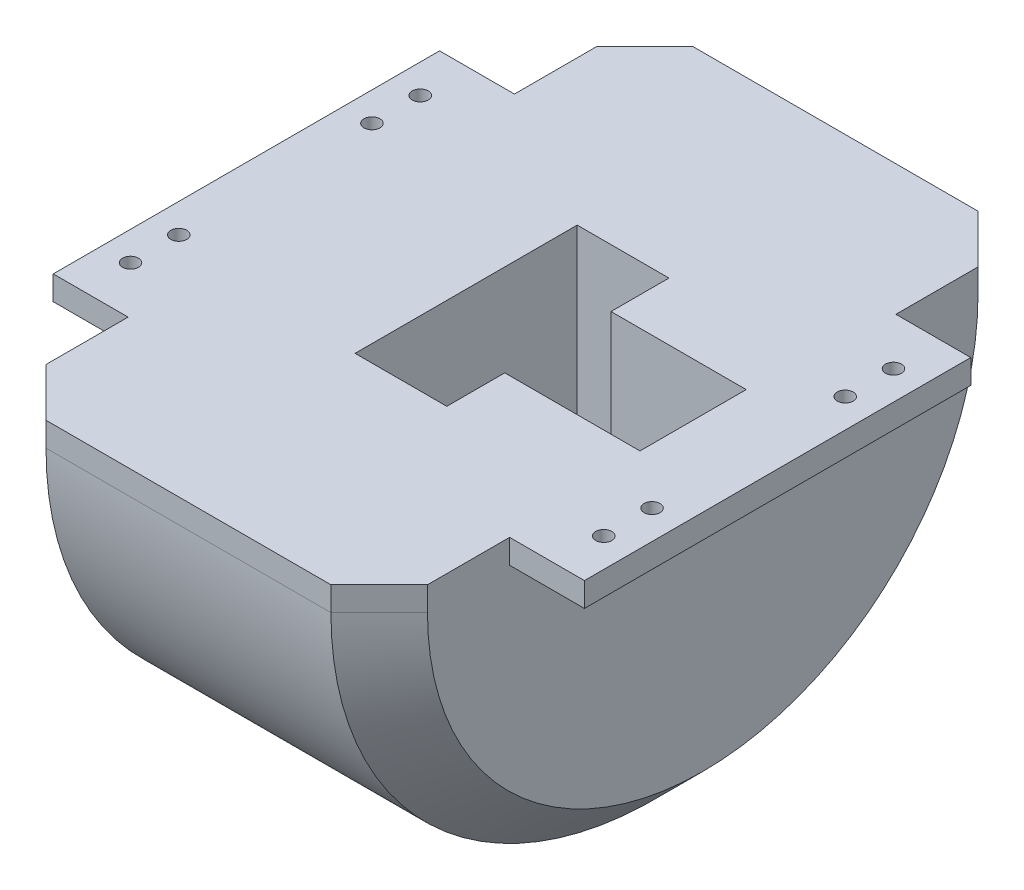
SolidWorks part; units mm, degrees
ref_plane "Front Plane" through (0, 0, 0) normal (0, 0, 1) x (1, 0, 0)
ref_plane "Top Plane" through (0, 0, 0) normal (0, 1, 0) x (1, 0, 0)
ref_plane "Right Plane" through (0, 0, 0) normal (1, 0, 0) x (0, 0, -1)
sketch "Sketch2" plane through (0, 0, 0) normal (0, 1, 0) x (1, 0, 0)
  line L0 (0, 0) -> (16.0378, 0) construction
  line L1 (-55, 40) -> (55, 40)
  line L2 (-55, 40) -> (-55, -40)
  line L3 (-55, -40) -> (55, -40)
  line L4 (55, 40) -> (55, -40)
  line L5 (-55, 40) -> (55, -40) construction
  line L6 (-55, -40) -> (55, 40) construction
  line L7 (0, 15.2625) -> (0, 0) construction
  line L8 (9.5, -11) -> (9.5, -23)
  line L9 (-9.5, 23) -> (9.5, 23)
  line L10 (-9.5, 23) -> (-9.5, -23)
  line L11 (-9.5, -23) -> (9.5, -23)
  line L12 (9.5, 23) -> (9.5, 11)
  line L13 (-9.5, 23) -> (9.5, -23) construction
  line L14 (-9.5, -23) -> (9.5, 23) construction
  line L15 (9.5, 11) -> (37.5, 11)
  line L17 (9.5, -11) -> (37.5, -11)
  line L18 (37.5, 11) -> (37.5, -11)
  circle A0 centre (-49, 30) radius 1.65
  circle A1 centre (-49, 20) radius 1.65
  circle A2 centre (49, 20) radius 1.65
  circle A3 centre (49, 30) radius 1.65
  circle A4 centre (49, -30) radius 1.65
  circle A5 centre (49, -20) radius 1.65
  circle A6 centre (-49, -30) radius 1.65
  circle A7 centre (-49, -20) radius 1.65
  point P0 (0, 0)
  dimension "D3" = 3.3
  dimension "D4" = 10
  dimension "D5" = 6
  dimension "D7" = 10
  dimension "D8" = 19
  dimension "D1" = 110
  dimension "D2" = 80
  dimension "D9" = 46
  dimension "D10" = 12
  dimension "D11" = 12
  dimension "D12" = 28
  dimension "D6" = 2
extrude "Boss-Extrude1" add sketch "Sketch2" along normal blind 5
sketch "Sketch4" plane through (0, 5, 0) normal (0, 1, 0) x (1, 0, 0)
  line L0 (55, 40) -> (-55, 40) construction
  line L1 (-39.5, 40) -> (39.5, 40)
  line L2 (-39.5, 40) -> (-39.5, 67)
  line L3 (-39.5, 67) -> (39.5, 67)
  line L4 (39.5, 40) -> (39.5, 67)
  line L10 (-9.5, 23) -> (-9.5, -23) construction
  line L11 (9.5, 11) -> (9.5, 23) construction
  line L12 (0, 0) -> (48.9802, 0) construction
  line L13 (39.5, -40) -> (39.5, -67)
  line L14 (-39.5, -67) -> (39.5, -67)
  line L15 (-39.5, -40) -> (-39.5, -67)
  line L16 (-39.5, -40) -> (39.5, -40)
  dimension "D1" = 30
  dimension "D2" = 30
  dimension "D3" = 27
extrude "Boss-Extrude2" add sketch "Sketch4" against normal blind 5
sketch "Sketch6" plane through (-39.5, 0, 0) normal (-1, 0, 0) x (0, 0, 1)
  line L0 (67, 0) -> (-67, 0) construction
  line L1 (-67, 0) -> (67, 0)
  arc A0 (-67, 0) -> (67, 0) centre (0, 0) ccw
extrude "Boss-Extrude3" add sketch "Sketch6" against normal blind 79
sketch "Sketch7" plane through (0, 0, 0) normal (0, 1, 0) x (1, 0, 0)
  line L1 (-9.5, -23) -> (9.5, -23)
  line L2 (-9.5, -23) -> (-9.5, 23)
  line L3 (-9.5, 23) -> (9.5, 23)
  line L4 (9.5, -23) -> (9.5, 23)
  line L5 (-9.5, -23) -> (9.5, 23) construction
  line L6 (-9.5, 23) -> (9.5, -23) construction
  line L7 (9.5, 11) -> (37.5, 11)
  line L8 (9.5, 11) -> (9.5, -11)
  line L9 (9.5, -11) -> (37.5, -11)
  line L10 (37.5, 11) -> (37.5, -11)
  point P0 (0, 0)
  line M1 (-9.5, 23) -> (-9.5, -23)
  line M2 (-9.5, -23) -> (9.5, -23)
  line M3 (9.5, -23) -> (9.5, -11)
  line M4 (9.5, -11) -> (37.5, -11)
  line M5 (37.5, -11) -> (37.5, 11)
  line M6 (37.5, 11) -> (9.5, 11)
  line M7 (9.5, 11) -> (9.5, 23)
  line M8 (9.5, 23) -> (-9.5, 23)
extrude "Cut-Extrude1" cut sketch "Sketch7" against normal blind 55.5 contours L4 M4 M5 M6 | L4 M3 M7 M8 M1 M2
chamfer "Chamfer1" distance 10 angle 45 6 edges at (39.5, 2.5, -67) (39.5, 2.5, 67) (-39.5, -67, 0) (39.5, -67, 0) (-39.5, 2.5, -67) (-39.5, 2.5, 67)
